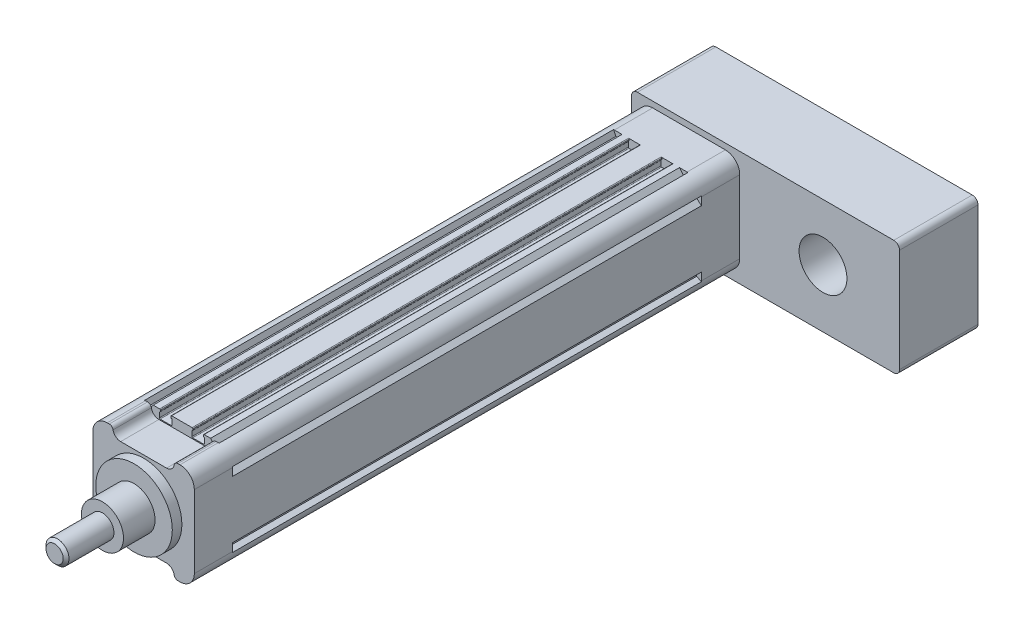
SolidWorks part; units mm, degrees
ref_plane "Front" through (0, 0, 0) normal (0, 0, 1) x (1, 0, 0)
ref_plane "Top" through (0, 0, 0) normal (0, 1, 0) x (1, 0, 0)
ref_plane "Right" through (0, 0, 0) normal (1, 0, 0) x (0, 0, -1)
sketch "草图1" plane through (0, 0, 0) normal (0, 0, 1) x (1, 0, 0)
  line L0 (19.7737, 3) -> (23.3, 3)
  line L1 (23.3, 3) -> (23.3, -3)
  line L2 (23.3, -3) -> (19.7737, -3)
  line L3 (-19.7737, -3) -> (-23.3, -3)
  line L4 (-23.3, -3) -> (-23.3, 3)
  line L5 (-23.3, 3) -> (-19.7737, 3)
  line L6 (-18.2, 24) -> (-19.4434, 26.4869)
  line L7 (-26.4869, 19.4434) -> (-24, 18.2)
  line L8 (-24, 18.2) -> (-24, 17.1)
  line L9 (-24, 17.1) -> (-26.5, 15)
  line L10 (-26.5, 15) -> (-26.5, -15)
  line L11 (-26.5, -15) -> (-24, -17.1)
  line L12 (-24, -17.1) -> (-24, -18.2)
  line L13 (-24, -18.2) -> (-26.4869, -19.4434)
  line L14 (-19.4434, -26.4869) -> (-18.2, -24)
  line L15 (-18.2, -24) -> (-17.1, -24)
  line L16 (-17.1, -24) -> (-15, -26.5)
  line L17 (-15, -26.5) -> (-11.65, -26.5)
  line L18 (-11.25, -26.1) -> (-11.25, -25.6)
  line L19 (-11.65, -25.2) -> (-11.75, -25.2)
  line L20 (-11.75, -25.2) -> (-11.75, -22.4)
  line L21 (-11.35, -22) -> (-5.65, -22)
  line L22 (-5.25, -22.4) -> (-5.25, -25.2)
  line L23 (-5.25, -25.2) -> (-5.35, -25.2)
  line L24 (-5.75, -25.6) -> (-5.75, -26.1)
  line L25 (-5.35, -26.5) -> (5.35, -26.5)
  line L26 (5.75, -26.1) -> (5.75, -25.6)
  line L27 (5.35, -25.2) -> (5.25, -25.2)
  line L28 (5.25, -25.2) -> (5.25, -22.4)
  line L29 (5.65, -22) -> (11.35, -22)
  line L30 (11.75, -22.4) -> (11.75, -25.2)
  line L31 (11.75, -25.2) -> (11.65, -25.2)
  line L32 (11.25, -25.6) -> (11.25, -26.1)
  line L33 (11.65, -26.5) -> (15, -26.5)
  line L34 (15, -26.5) -> (17.1, -24)
  line L35 (17.1, -24) -> (18.2, -24)
  line L36 (18.2, -24) -> (19.4434, -26.4869)
  line L37 (26.4869, -19.4434) -> (24, -18.2)
  line L38 (24, -18.2) -> (24, -17.1)
  line L39 (24, -17.1) -> (26.5, -15)
  line L40 (26.5, -15) -> (26.5, 15)
  line L41 (26.5, 15) -> (24, 17.1)
  line L42 (24, 17.1) -> (24, 18.2)
  line L43 (24, 18.2) -> (26.4869, 19.4434)
  line L44 (19.4434, 26.4869) -> (18.2, 24)
  line L45 (18.2, 24) -> (17.1, 24)
  line L46 (17.1, 24) -> (15, 26.5)
  line L47 (15, 26.5) -> (11.65, 26.5)
  line L48 (11.25, 26.1) -> (11.25, 25.6)
  line L49 (11.65, 25.2) -> (11.75, 25.2)
  line L50 (11.75, 25.2) -> (11.75, 22.4)
  line L51 (11.35, 22) -> (5.65, 22)
  line L52 (5.25, 22.4) -> (5.25, 25.2)
  line L53 (5.25, 25.2) -> (5.35, 25.2)
  line L54 (5.75, 25.6) -> (5.75, 26.1)
  line L55 (5.35, 26.5) -> (-5.35, 26.5)
  line L56 (-5.75, 26.1) -> (-5.75, 25.6)
  line L57 (-5.35, 25.2) -> (-5.25, 25.2)
  line L58 (-5.25, 25.2) -> (-5.25, 22.4)
  line L59 (-5.65, 22) -> (-11.35, 22)
  line L60 (-11.75, 22.4) -> (-11.75, 25.2)
  line L61 (-11.75, 25.2) -> (-11.65, 25.2)
  line L62 (-11.25, 25.6) -> (-11.25, 26.1)
  line L63 (-11.65, 26.5) -> (-15, 26.5)
  line L64 (-15, 26.5) -> (-17.1, 24)
  line L65 (-17.1, 24) -> (-18.2, 24)
  arc A0 (19.7737, 3) -> (-19.7737, 3) centre (0, 0) ccw
  arc A1 (-19.7737, -3) -> (19.7737, -3) centre (0, 0) ccw
  circle A2 centre (19, 19) radius 2.1
  circle A3 centre (19, -19) radius 2.1
  circle A4 centre (-19, -19) radius 2.1
  circle A5 centre (-19, 19) radius 2.1
  arc A6 (-19.4434, 26.4869) -> (-26.4869, 19.4434) centre (-19, 19) ccw
  arc A7 (-26.4869, -19.4434) -> (-19.4434, -26.4869) centre (-19, -19) ccw
  arc A8 (-11.65, -26.5) -> (-11.25, -26.1) centre (-11.65, -26.1) ccw
  arc A9 (-11.25, -25.6) -> (-11.65, -25.2) centre (-11.65, -25.6) ccw
  arc A10 (-11.35, -22) -> (-11.75, -22.4) centre (-11.35, -22.4) ccw
  arc A11 (-5.25, -22.4) -> (-5.65, -22) centre (-5.65, -22.4) ccw
  arc A12 (-5.35, -25.2) -> (-5.75, -25.6) centre (-5.35, -25.6) ccw
  arc A13 (-5.75, -26.1) -> (-5.35, -26.5) centre (-5.35, -26.1) ccw
  arc A14 (5.35, -26.5) -> (5.75, -26.1) centre (5.35, -26.1) ccw
  arc A15 (5.75, -25.6) -> (5.35, -25.2) centre (5.35, -25.6) ccw
  arc A16 (5.65, -22) -> (5.25, -22.4) centre (5.65, -22.4) ccw
  arc A17 (11.75, -22.4) -> (11.35, -22) centre (11.35, -22.4) ccw
  arc A18 (11.65, -25.2) -> (11.25, -25.6) centre (11.65, -25.6) ccw
  arc A19 (11.25, -26.1) -> (11.65, -26.5) centre (11.65, -26.1) ccw
  arc A20 (19.4434, -26.4869) -> (26.4869, -19.4434) centre (19, -19) ccw
  arc A21 (26.4869, 19.4434) -> (19.4434, 26.4869) centre (19, 19) ccw
  arc A22 (11.65, 26.5) -> (11.25, 26.1) centre (11.65, 26.1) ccw
  arc A23 (11.25, 25.6) -> (11.65, 25.2) centre (11.65, 25.6) ccw
  arc A24 (11.35, 22) -> (11.75, 22.4) centre (11.35, 22.4) ccw
  arc A25 (5.25, 22.4) -> (5.65, 22) centre (5.65, 22.4) ccw
  arc A26 (5.35, 25.2) -> (5.75, 25.6) centre (5.35, 25.6) ccw
  arc A27 (5.75, 26.1) -> (5.35, 26.5) centre (5.35, 26.1) ccw
  arc A28 (-5.35, 26.5) -> (-5.75, 26.1) centre (-5.35, 26.1) ccw
  arc A29 (-5.75, 25.6) -> (-5.35, 25.2) centre (-5.35, 25.6) ccw
  arc A30 (-5.65, 22) -> (-5.25, 22.4) centre (-5.65, 22.4) ccw
  arc A31 (-11.75, 22.4) -> (-11.35, 22) centre (-11.35, 22.4) ccw
  arc A32 (-11.65, 25.2) -> (-11.25, 25.6) centre (-11.65, 25.6) ccw
  arc A33 (-11.25, 26.1) -> (-11.65, 26.5) centre (-11.65, 26.1) ccw
extrude "凸台-拉伸1" add sketch "草图1" along normal blind 245
sketch "草图6" plane through (0, 0, 245) normal (0, 0, 1) x (1, 0, 0)
  line L0 (0, 0) -> (19, 0) construction
  line L2 (-26.5, -19) -> (-26.5, 19)
  line L3 (-19, 26.5) -> (-17.9161, 26.5)
  line L4 (26.5, -19) -> (26.5, 19)
  line L5 (-26.5, -26.5) -> (26.5, 26.5) construction
  line L6 (-26.5, 26.5) -> (26.5, -26.5) construction
  line L7 (-12, 21.5) -> (12, 21.5)
  line L9 (19, 26.5) -> (17.9161, 26.5)
  line L10 (19, -26.5) -> (17.9161, -26.5)
  line L11 (-12, -21.5) -> (12, -21.5)
  line L12 (-19, -26.5) -> (-17.9161, -26.5)
  arc A0 (12, 21.5) -> (15.9441, 24.8333) centre (12, 25.5) ccw
  arc A1 (-15.9441, 24.8333) -> (-12, 21.5) centre (-12, 25.5) ccw
  arc A2 (-15.9441, 24.8333) -> (-17.9161, 26.5) centre (-17.9161, 24.5) ccw
  arc A3 (15.9441, 24.8333) -> (17.9161, 26.5) centre (17.9161, 24.5) cw
  arc A4 (-26.5, -19) -> (-19, -26.5) centre (-19, -19) ccw
  arc A5 (19, -26.5) -> (26.5, -19) centre (19, -19) ccw
  arc A6 (26.5, 19) -> (19, 26.5) centre (19, 19) ccw
  arc A7 (-26.5, 19) -> (-19, 26.5) centre (-19, 19) cw
  arc A8 (15.9441, -24.8333) -> (17.9161, -26.5) centre (17.9161, -24.5) ccw
  arc A9 (12, -21.5) -> (15.9441, -24.8333) centre (12, -25.5) cw
  arc A10 (-15.9441, -24.8333) -> (-12, -21.5) centre (-12, -25.5) cw
  arc A11 (-15.9441, -24.8333) -> (-17.9161, -26.5) centre (-17.9161, -24.5) cw
  point P0 (0, 0)
  point P9 (0, 21.5)
  point P13 (20, 20.8461)
  point P16 (-12, 20.8461)
  dimension "D5" = 4
  dimension "D6" = 2
  dimension "D7" = 2
  dimension "D9" = 7.5
  dimension "D1" = 53
  dimension "D2" = 53
  dimension "D3" = 26.5
  dimension "D4" = 24
  dimension "D8" = 5
extrude "凸台-拉伸2" add sketch "草图6" along normal blind 20
sketch "草图7" plane through (0, 0, 265) normal (0, 0, 1) x (1, 0, 0)
  circle A0 centre (0, 0) radius 20
  dimension "D1" = 40
extrude "凸台-拉伸3" add sketch "草图7" along normal blind 5
sketch "草图9" plane through (0, 0, 270) normal (0, 0, 1) x (1, 0, 0)
  circle A0 centre (0, 0) radius 11
  dimension "D1" = 22
extrude "凸台-拉伸4" add sketch "草图9" along normal blind 16.5
sketch "草图10" plane through (0, 0, 286.5) normal (0, 0, 1) x (1, 0, 0)
  circle A0 centre (0, 0) radius 6
  dimension "D1" = 12
extrude "凸台-拉伸5" add sketch "草图10" along normal blind 25
sketch "草图11" plane through (0, 0, 0) normal (0, 0, -1) x (-1, 0, 0)
  line L1 (-19, -26.5) -> (19, -26.5)
  line L2 (-26.5, -19) -> (-26.5, 19)
  line L3 (-19, 26.5) -> (19, 26.5)
  line L4 (26.5, -19) -> (26.5, 19)
  line L5 (-26.5, -26.5) -> (26.5, 26.5) construction
  line L6 (-26.5, 26.5) -> (26.5, -26.5) construction
  arc A0 (-26.5, -19) -> (-19, -26.5) centre (-19, -19) ccw
  arc A1 (19, -26.5) -> (26.5, -19) centre (19, -19) ccw
  arc A2 (26.5, 19) -> (19, 26.5) centre (19, 19) ccw
  arc A3 (-26.5, 19) -> (-19, 26.5) centre (-19, 19) cw
  point P0 (0, 0)
  dimension "D3" = 7.5
  dimension "D1" = 53
  dimension "D2" = 53
extrude "凸台-拉伸6" add sketch "草图11" along normal blind 20
sketch "草图12" plane through (0, 0, -20) normal (0, 0, -1) x (-1, 0, 0)
  line L1 (-107, -30.4042) -> (27, -30.4042)
  line L2 (-110, -27.4042) -> (-110, 26.5958)
  line L3 (-107, 29.5958) -> (27, 29.5958)
  line L4 (30, -27.4042) -> (30, 26.5958)
  line L5 (-110, -30.4042) -> (30, 29.5958) construction
  line L6 (-110, 29.5958) -> (30, -30.4042) construction
  arc A0 (27, 29.5958) -> (30, 26.5958) centre (27, 26.5958) cw
  arc A1 (30, -27.4042) -> (27, -30.4042) centre (27, -27.4042) cw
  arc A2 (-110, -27.4042) -> (-107, -30.4042) centre (-107, -27.4042) ccw
  arc A3 (-110, 26.5958) -> (-107, 29.5958) centre (-107, 26.5958) cw
  point P0 (-40, -0.4042)
  dimension "D4" = 3
  dimension "D1" = 60
  dimension "D2" = 140
  dimension "D3" = 30
extrude "凸台-拉伸7" add sketch "草图12" along normal blind 41
sketch "草图13" plane through (0, 0, -20) normal (0, 0, 1) x (1, 0, 0)
  circle A0 centre (70, 0) radius 12.5
  dimension "D2" = 25
  dimension "D1" = 70
extrude "切除-拉伸2" cut sketch "草图13" against normal blind 30
hole_wizard "M6 螺纹孔1" positions "草图14" profile "草图15" tap size "M6" standard "GB"
sketch "草图14" plane through (0, 0, -61) normal (0, 0, -1) x (-1, 0, 0)
  line L0 (30, -27.4042) -> (30, 26.5958) construction
  point P0 (19, -19)
  dimension "D1" = 11
  dimension "D2" = 19
sketch "草图15" plane through (-19, -19, -61) normal (1, 0, 0) x (0, 1, 0)
  line L0 (0, 0) -> (0, 16.5022)
  line L1 (0, 16.5022) -> (2.5, 15)
  line L2 (2.5, 15) -> (2.5, 0)
  line L5 (2.5, 0) -> (0, 0)
  line L10 (0, 16.5022) -> (-2.5, 15) construction
  line L11 (0, -6.35) -> (0, 107.95) construction
  dimension "螺纹孔钻头直径" = 5
  dimension "螺纹孔钻头深度" = 15
  dimension "导头角度" = 118
cosmetic thread "孔螺蚊线4" parameters "D1"=12, "D2"=6
pattern_linear "阵列(线性)1" count 2 spacing 38 along (0, 1, 0) count 2 spacing 38 along (1, 0, 0) of "M6 螺纹孔1"
hole_wizard "M6 螺纹孔2" positions "草图16" profile "草图17" tap size "M6" standard "GB"
sketch "草图16" plane through (0, 0, -61) normal (0, 0, -1) x (-1, 0, 0)
  circle A1 centre (-19, 19) radius 2.5 construction
  circle A2 centre (-19, -19) radius 2.5 construction
  point P0 (-84, -19)
  point P2 (-84, 19)
  dimension "D3" = 65
  dimension "D1" = 19
  dimension "D2" = 19
  dimension "D4" = 65
sketch "草图17" plane through (84, -19, -61) normal (1, 0, 0) x (0, 1, 0)
  line L0 (0, 0) -> (0, 16.5022)
  line L1 (0, 16.5022) -> (2.5, 15)
  line L2 (2.5, 15) -> (2.5, 0)
  line L5 (2.5, 0) -> (0, 0)
  line L10 (0, 16.5022) -> (-2.5, 15) construction
  line L11 (0, -6.35) -> (0, 107.95) construction
  dimension "螺纹孔钻头直径" = 5
  dimension "螺纹孔钻头深度" = 15
  dimension "导头角度" = 118
cosmetic thread "孔螺蚊线5" parameters "D1"=12, "D2"=6
cosmetic thread "孔螺蚊线6" parameters "D1"=12, "D2"=6
hole_wizard "M6 螺纹孔3" positions "草图19" profile "草图20" tap size "M6" standard "GB"
sketch "草图19" plane through (-26.5, 0, 0) normal (-1, 0, 0) x (0, 0, 1)
  line L0 (265, 19) -> (265, -19) construction
  point P0 (255, 11)
  point P2 (255, -11)
  dimension "D1" = 10
  dimension "D2" = 10
  dimension "D3" = 22
  dimension "D4" = 11
sketch "草图20" plane through (-26.5, 11, 255) normal (0, 1, 0) x (0, 0, 1)
  line L0 (0, 0) -> (0, 16.5022)
  line L1 (0, 16.5022) -> (2.5, 15)
  line L2 (2.5, 15) -> (2.5, 0)
  line L5 (2.5, 0) -> (0, 0)
  line L10 (0, 16.5022) -> (-2.5, 15) construction
  line L11 (0, -6.35) -> (0, 107.95) construction
  dimension "螺纹孔钻头直径" = 5
  dimension "螺纹孔钻头深度" = 15
  dimension "导头角度" = 118
cosmetic thread "孔螺蚊线7" parameters "D1"=12, "D2"=6
cosmetic thread "孔螺蚊线8" parameters "D1"=12, "D2"=6
hole_wizard "M6 螺纹孔4" positions "草图21" profile "草图22" tap size "M6" standard "GB"
sketch "草图21" plane through (-26.5, 0, 0) normal (-1, 0, 0) x (0, 0, 1)
  line L0 (-20, -27.4042) -> (-20, 26.5958) construction
  line L1 (-20, -19) -> (-20, 19) construction
  point P0 (-10, 11)
  point P2 (-10, -11)
  dimension "D1" = 10
  dimension "D2" = 10
  dimension "D3" = 11
  dimension "D4" = 11
sketch "草图22" plane through (-26.5, 11, -10) normal (0, 1, 0) x (0, 0, 1)
  line L0 (0, 0) -> (0, 16.5022)
  line L1 (0, 16.5022) -> (2.5, 15)
  line L2 (2.5, 15) -> (2.5, 0)
  line L5 (2.5, 0) -> (0, 0)
  line L10 (0, 16.5022) -> (-2.5, 15) construction
  line L11 (0, -6.35) -> (0, 107.95) construction
  dimension "螺纹孔钻头直径" = 5
  dimension "螺纹孔钻头深度" = 15
  dimension "导头角度" = 118
cosmetic thread "孔螺蚊线9" parameters "D1"=12, "D2"=6
cosmetic thread "孔螺蚊线10" parameters "D1"=12, "D2"=6
chamfer "倒角1" distance 1.5 angle 45 1 edges at (6, 0, 311.5)
sketch "草图23" plane through (0, 0, 286.5) normal (0, 0, 1) x (1, 0, 0)
  line L1 (10.9697, 0) -> (5.4848, 9.5)
  line L2 (5.4848, 9.5) -> (-5.4848, 9.5)
  line L3 (-5.4848, 9.5) -> (-10.9697, 0)
  line L4 (-10.9697, 0) -> (-5.4848, -9.5)
  line L5 (-5.4848, -9.5) -> (5.4848, -9.5)
  line L6 (5.4848, -9.5) -> (10.9697, 0)
  circle A0 centre (0, 0) radius 9.5 construction
  dimension "D1" = 19
